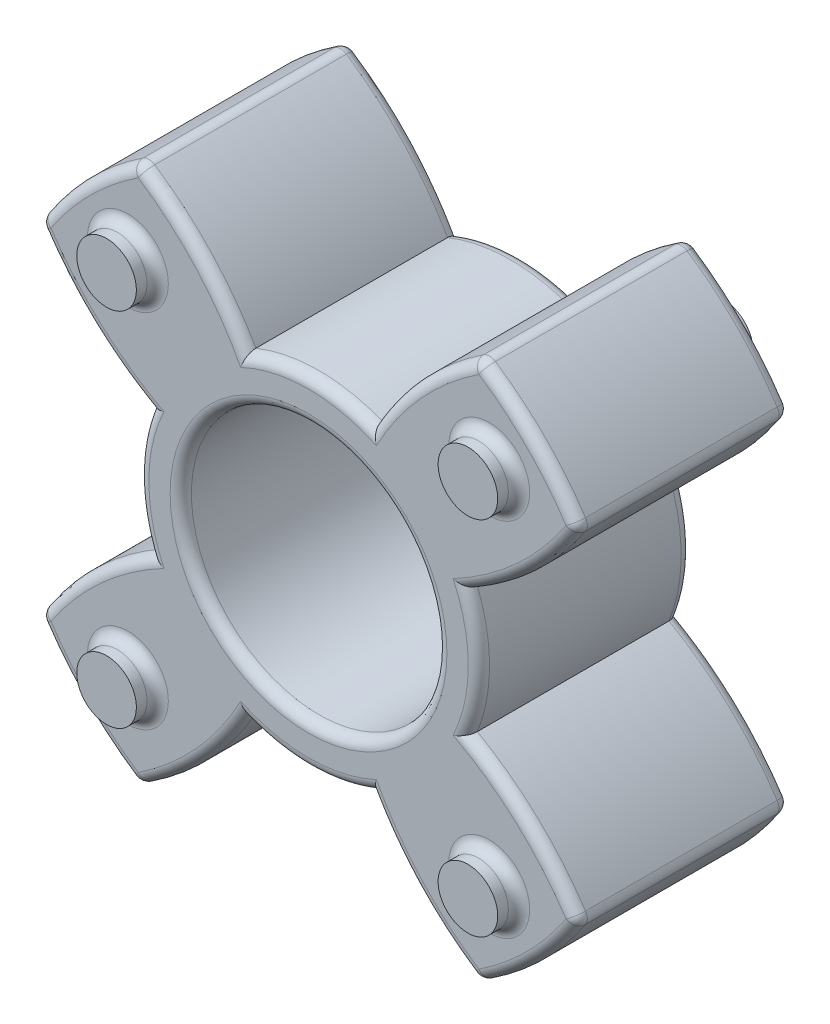
SolidWorks part; units mm, degrees
ref_plane "Front Plane" through (0, 0, 0) normal (0, 0, 1) x (1, 0, 0)
ref_plane "Top Plane" through (0, 0, 0) normal (0, 1, 0) x (1, 0, 0)
ref_plane "Right Plane" through (0, 0, 0) normal (1, 0, 0) x (0, 0, -1)
sketch "Sketch1" plane through (0, 0, 0) normal (0, 0, 1) x (1, 0, 0)
  line L0 (-16, 0) -> (0, 0) construction
  circle A0 centre (0, 0) radius 6
  arc A1 (-7.4288, 2.9687) -> (-7.4288, -2.9688) centre (0, 0) ccw
  arc A2 (-8, -12.6886) -> (-2.9688, -7.4288) centre (-16, 0) ccw
  arc A3 (-8, 12.6886) -> (-12.6886, 8) centre (0, 0) ccw
  arc A4 (-12.6886, 8) -> (-7.4288, 2.9687) centre (0, 16) ccw
  arc A5 (8, 12.6886) -> (2.9688, 7.4288) centre (16, 0) ccw
  arc A6 (12.6886, -8) -> (7.4288, -2.9687) centre (0, -16) ccw
  arc A7 (12.6886, 8) -> (8, 12.6886) centre (0, 0) ccw
  arc A8 (8, -12.6886) -> (12.6886, -8) centre (0, 0) ccw
  arc A9 (-12.6886, -8) -> (-8, -12.6886) centre (0, 0) ccw
  arc A10 (-7.4288, -2.9688) -> (-12.6886, -8) centre (0, -16) ccw
  arc A11 (-2.0938, -5.6228) -> (-2.0938, 5.6228) centre (-16, 0) ccw construction
  arc A12 (2.9688, -7.4288) -> (8, -12.6886) centre (16, 0) ccw
  arc A13 (5.6228, -2.0938) -> (-5.6228, -2.0938) centre (0, -16) ccw construction
  arc A14 (7.4288, 2.9687) -> (12.6886, 8) centre (0, 16) ccw
  arc A15 (2.0938, 5.6228) -> (2.0938, -5.6228) centre (16, 0) ccw construction
  arc A16 (-2.9688, 7.4288) -> (-8, 12.6886) centre (-16, 0) ccw
  arc A17 (-5.6228, 2.0937) -> (5.6228, 2.0937) centre (0, 16) ccw construction
  arc A18 (2.9688, 7.4288) -> (-2.9688, 7.4288) centre (0, 0) ccw
  arc A19 (7.4288, -2.9687) -> (7.4288, 2.9687) centre (0, 0) ccw
  arc A20 (-2.9688, -7.4288) -> (2.9688, -7.4288) centre (0, 0) ccw
  point P6 (19.0094, 1.2262)
  point P7 (0, 0)
  point P16 (0, 0)
  dimension "D1" = 12
  dimension "D2" = 16
  dimension "D3" = 30
  dimension "D6" = 15
  dimension "D4" = 16
  dimension "D5" = 4
extrude "Boss-Extrude1" add sketch "Sketch1" along normal mid plane 10
sketch "Sketch2" plane through (0, 0, 5) normal (0, 0, 1) x (1, 0, 0)
  line L0 (0, 0) -> (-10.6066, 10.6066) construction
  arc A0 (-8, 12.6886) -> (-12.6886, 8) centre (0, 0) ccw construction
  circle A1 centre (-8.4853, 8.4853) radius 1.4
  circle A2 centre (8.4853, 8.4853) radius 1.4
  circle A3 centre (8.4853, -8.4853) radius 1.4
  circle A4 centre (-8.4853, -8.4853) radius 1.4
  point P3 (0, 0)
  point P9 (8.4853, 8.4853)
  point P17 (0, 0)
  dimension "D1" = 2.8
  dimension "D2" = 12
  dimension "D3" = 4
extrude "Boss-Extrude2" add sketch "Sketch2" against normal offset from surface (12 mm away) 1 from offset 1 up to face at (0, 0, -5) offset beyond the face yes
fillet "Fillet1" radius 0.5 50 edges at (-12.6886, -8, 0) (-8, -12.6886, 0) (-8, 12.6886, 0) (-12.6886, 8, 0) (8, -12.6886, 0) (12.6886, -8, 0) (12.6886, 8, 0) (8, 12.6886, 0) (6, 0, -5) (-10.6066, -10.6066, -5) (-5.1605, -10.3685, -5) (0, -8, -5) (5.1605, -10.3685, -5) (10.6066, -10.6066, -5) (10.3685, -5.1605, -5) (8, 0, -5) (10.3685, 5.1605, -5) (10.6066, 10.6066, -5) (5.1605, 10.3685, -5) (0, 8, -5) (-5.1605, 10.3685, -5) (-10.6066, 10.6066, -5) (-10.3685, 5.1605, -5) (-8, 0, -5) (-10.3685, -5.1605, -5) (-7.0853, 8.4853, -5) (9.8853, 8.4853, -5) (9.8853, -8.4853, -5) (-7.0853, -8.4853, -5) (6, 0, 5) (-8, 0, 5) (-10.3685, 5.1605, 5) (-10.6066, 10.6066, 5) (-5.1605, 10.3685, 5) (0, 8, 5) (5.1605, 10.3685, 5) (10.6066, 10.6066, 5) (10.3685, 5.1605, 5) (8, 0, 5) (10.3685, -5.1605, 5) (10.6066, -10.6066, 5) (5.1605, -10.3685, 5) (0, -8, 5) (-5.1605, -10.3685, 5) (-10.6066, -10.6066, 5) (-10.3685, -5.1605, 5) (-7.0853, 8.4853, 5) (9.8853, 8.4853, 5) (9.8853, -8.4853, 5) (-7.0853, -8.4853, 5)
